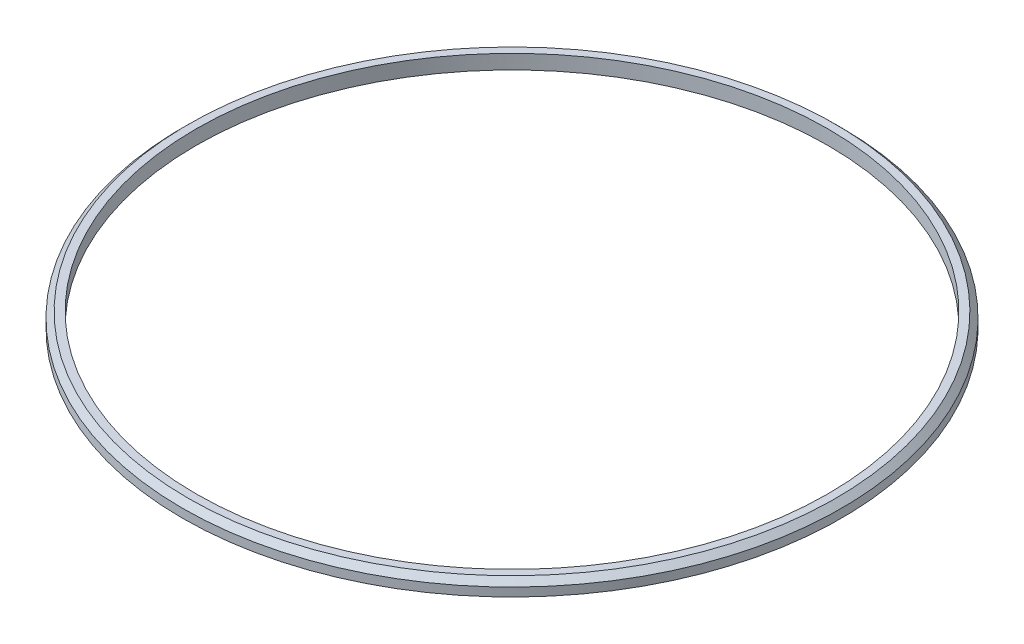
SolidWorks part; units mm, degrees
material "PETG"
ref_plane "Front Plane" through (0, 0, 0) normal (0, 0, 1) x (1, 0, 0)
ref_plane "Top Plane" through (0, 0, 0) normal (0, 1, 0) x (1, 0, 0)
ref_plane "Right Plane" through (0, 0, 0) normal (1, 0, 0) x (0, 0, -1)
sketch "Sketch1" plane through (0, 0, 0) normal (0, 1, 0) x (1, 0, 0)
  circle A0 centre (0, 0) radius 57.225
  circle A1 centre (0, 0) radius 54.875
  dimension "Ring OD" = 114.45
  dimension "Ring Width" = 2.35
extrude "Boss-Extrude1" add sketch "Sketch1" along normal blind 2.5
chamfer "Chamfer1" distance 1 angle 45 1 edges at (0, 2.5, 57.225)
equation "\"tol_dia_id_intfc\" = 0.0500mm ' For hole diameters - Interference fit"
equation "\"tol_dia_id_slip\"  = 0.0750mm ' For hole diameters - Slip fit"
equation "\"tol_dia_id_clear\" = 0.1000mm ' For hole diameters - Clearance fit"
equation "\"tol_dia_od_intfc\" = 0.0500mm ' For shaft diameters - Interference fit"
equation "\"tol_dia_od_slip\"  = 0.0750mm ' For shaft diameters - Slip fit"
equation "\"tol_dia_od_clear\" = 0.1000mm ' For shaft diameters - Clearance fit"
equation "\"tol_general_intfc\"= 0.0250mm ' For general parts (Horiz) - Interference fit"
equation "\"tol_general_slip\" = 0.0375mm ' For general parts (Horiz) - Slip fit"
equation "\"tol_general_clear\"= 0.0500mm ' For general parts (Horiz) - Clearance fit"
equation "\"tol_layer_intfc\"  = 0.0250mm ' For all parts (Vert) - Interference fit"
equation "\"tol_layer_slip\"   = 0.0375mm ' For all parts (Vert) - Slip fit"
equation "\"tol_layer_clear\"  = 0.0500mm ' For all parts (Vert) - Clearance fit"
equation "\"tol_corner_rad\"   = 0.100mm ' For corners that fit into other parts"
equation "\"Ring OD@Sketch1\" = 114.50mm - \"tol_dia_od_intfc\""
equation "\"Ring Width@Sketch1\" = 2.50mm - \"tol_dia_id_slip\" - \"tol_dia_od_slip\""
